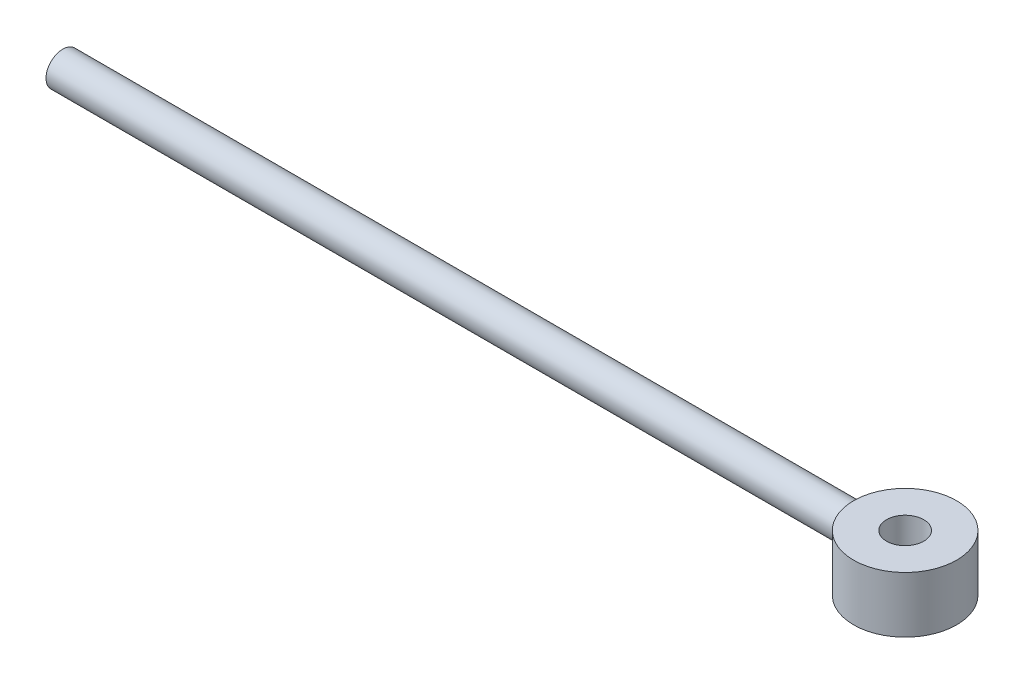
SolidWorks part; units mm, degrees
ref_plane "前视基准面" through (0, 0, 0) normal (0, 0, 1) x (1, 0, 0)
ref_plane "上视基准面" through (0, 0, 0) normal (0, 1, 0) x (1, 0, 0)
ref_plane "右视基准面" through (0, 0, 0) normal (1, 0, 0) x (0, 0, -1)
sketch "草图1" plane through (0, 0, 0) normal (1, 0, 0) x (0, 0, -1)
  circle A0 centre (0, 0) radius 0.6
  dimension "D1" = 1.2
extrude "凸台-拉伸1" add sketch "草图1" along normal blind 30
sketch "草图2" plane through (8.3794, -0.2457, -12) normal (0, 1, 0) x (1, 0, 0)
  circle A0 centre (21.667, -12) radius 1.8378
extrude "凸台-拉伸2" add sketch "草图2" along normal mid plane 2
sketch "草图3" plane through (0, -1.2457, 0) normal (0, -1, 0) x (-1, 0, 0)
  circle A0 centre (-30.0464, 0) radius 0.6657
extrude "切除-拉伸1" cut sketch "草图3" against normal through all
